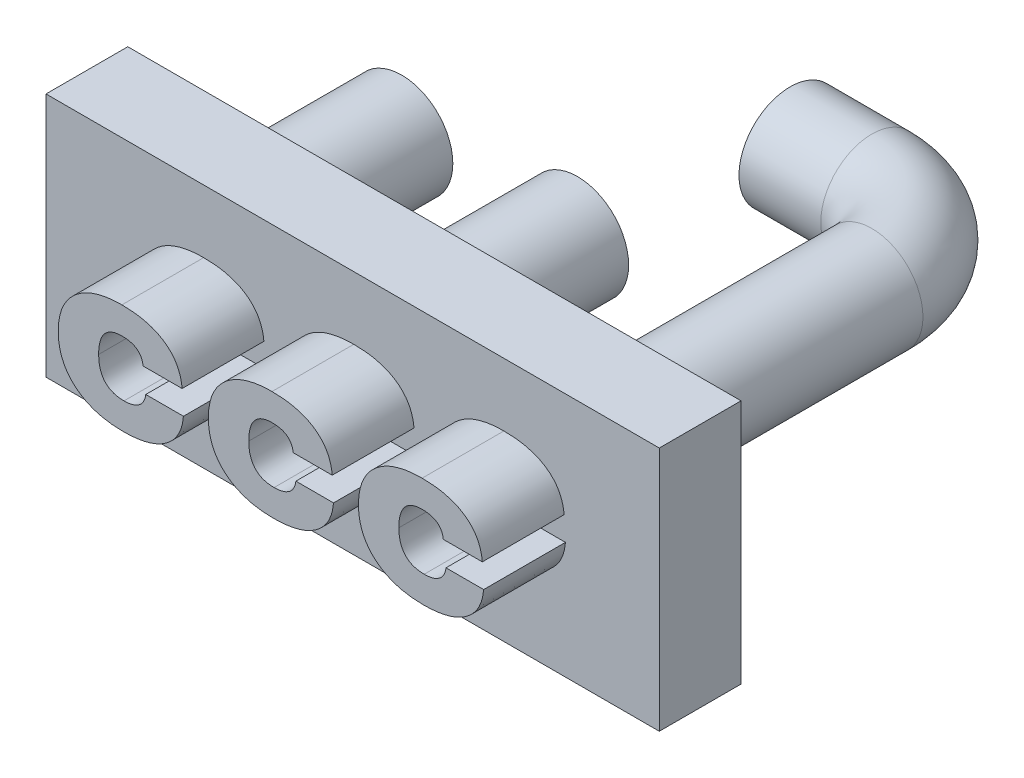
SolidWorks part; units mm, degrees
ref_plane "Front Plane" through (0, 0, 0) normal (0, 0, 1) x (1, 0, 0)
ref_plane "Top Plane" through (0, 0, 0) normal (0, 1, 0) x (1, 0, 0)
ref_plane "Right Plane" through (0, 0, 0) normal (1, 0, 0) x (0, 0, -1)
sketch "Sketch1" plane through (0, 0, 0) normal (0, 0, 1) x (1, 0, 0)
  line L1 (-7.5, 3) -> (7.5, 3)
  line L2 (-7.5, 3) -> (-7.5, -3)
  line L3 (-7.5, -3) -> (7.5, -3)
  line L4 (7.5, 3) -> (7.5, -3)
  line L5 (-7.5, 3) -> (7.5, -3) construction
  line L6 (-7.5, -3) -> (7.5, 3) construction
  point P0 (0, 0)
  dimension "D1" = 15
  dimension "D2" = 6
extrude "Boss-Extrude1" add sketch "Sketch1" along normal blind 2
sketch "Sketch2" plane through (0, 0, 2) normal (0, 0, 1) x (1, 0, 0)
  text T0 "CCC" font "Swis721 Blk BT" height in points 10
extrude "Boss-Extrude2" add sketch "Sketch2" along normal blind 2
sketch "Sketch8" plane through (0, 0, 0) normal (0, 0, -1) x (-1, 0, 0)
  line L0 (2.2, 0) -> (-2.2, 0) construction
  line L1 (0, 0) -> (0, 0.75) construction
  line L3 (0, 3) -> (0, -3) construction
  line L4 (-7.5, 3) -> (7.5, 3) construction
  line L5 (7.5, -3) -> (-7.5, -3) construction
  circle A0 centre (1, 0) radius 1.25
  circle A1 centre (-3.7443, 0) radius 1.25 construction
  dimension "D1" = 2.5
  dimension "D2" = 2.5
  dimension "D3" = 1
extrude "Boss-Extrude4" add sketch "Sketch8" along normal blind 4.5
sketch "Sketch7" plane through (0, 0, 0) normal (0, 0, -1) x (-1, 0, 0)
  line L0 (4.675, 0) -> (-4.675, 0) construction
  circle A0 centre (5.3, 0) radius 1.25
  dimension "D1" = 2.5
  dimension "D2" = 5.3
extrude "Boss-Extrude5" add sketch "Sketch7" along normal blind 4.5
sketch "Sketch9" plane through (0, 0, 0) normal (0, 1, 0) x (1, 0, 0)
  line L0 (3.6987, -2) -> (3.6987, 9) construction
  line L1 (7.5, 0) -> (-7.5, 0) construction
  line L2 (3.6987, 9) -> (-0.3013, 9) construction
  line L3 (3.6987, -0.2249) -> (3.6987, 7)
  line L4 (-0.3013, 9) -> (1.6987, 9)
  arc A0 (3.6987, 7) -> (1.6987, 9) centre (1.6987, 7) ccw
  dimension "D2" = 2
  dimension "D1" = 9
  dimension "D3" = 2
sketch "Sketch10" plane through (0, 0, 0) normal (0, 0, -1) x (-1, 0, 0)
  line L0 (-1.6987, 0) -> (-3.6987, 0) construction
  line L1 (-3.6987, 0) -> (0.3013, 0) construction
  circle A0 centre (-3.6987, 0) radius 1.25
  dimension "D1" = 2.5
sweep "Sweep4" add profiles "Sketch10" path "Sketch9"
